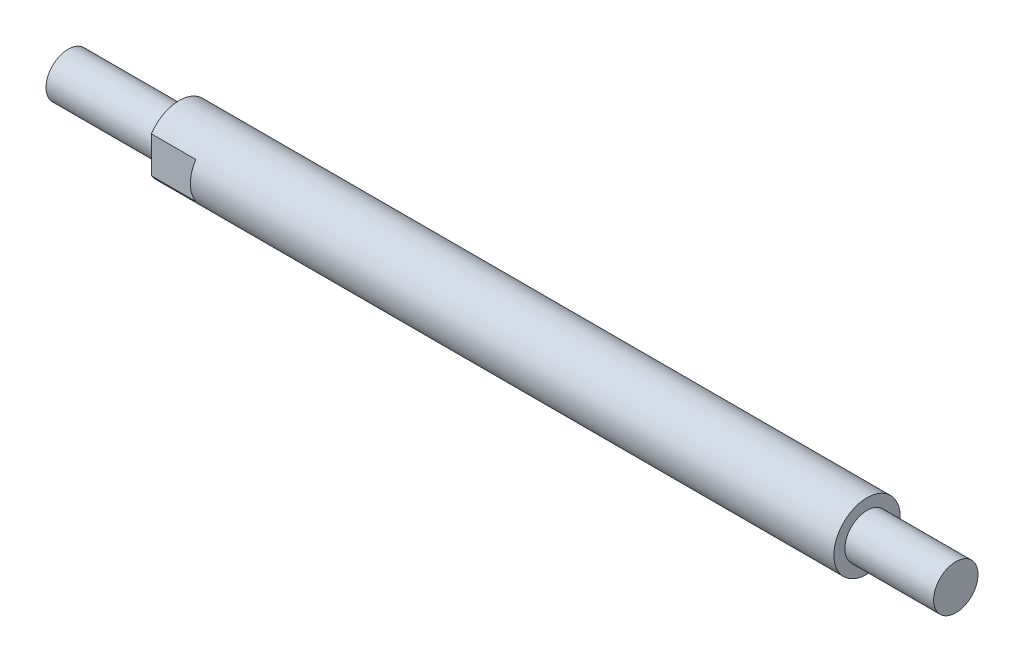
SolidWorks part; units mm, degrees
ref_plane "Front" through (0, 0, 0) normal (0, 0, 1) x (1, 0, 0)
ref_plane "Top" through (0, 0, 0) normal (0, 1, 0) x (1, 0, 0)
ref_plane "Right" through (0, 0, 0) normal (1, 0, 0) x (0, 0, -1)
sketch "Sketch1" plane through (0, 0, 0) normal (1, 0, 0) x (0, 0, -1)
  circle A0 centre (0, 0) radius 4.745
  dimension "D1" = 9.49
extrude "Base-Extrude" add sketch "Sketch1" along normal blind 114.3
sketch "Sketch2" plane through (114.3, 0, 0) normal (1, 0, 0) x (0, 0, -1)
  circle A0 centre (0, 0) radius 3.175
  dimension "D1" = 6.35
extrude "Boss-Extrude1" add sketch "Sketch2" along normal blind 12.7
cosmetic thread "Cosmetic Thread1" parameters "D2"=5.1054
sketch "Sketch3" plane through (0, 0, 0) normal (-1, 0, 0) x (0, 0, 1)
  circle A0 centre (0, 0) radius 3.175
  circle A2 centre (0, 0) radius 4.745
  circle A3 centre (0, 0) radius 4.745
  dimension "D1" = 6.35
  dimension "D2" = 0
extrude "Cut-Extrude1" cut sketch "Sketch3" against normal blind 15.875
sketch "Sketch4" plane through (15.875, 0, 0) normal (-1, 0, 0) x (0, 0, 1)
  line L1 (3.9688, 2.6008) -> (3.9688, -2.6008)
  line L3 (-3.9688, -2.6008) -> (-3.9688, 2.6008)
  line L4 (0, 4.7625) -> (0, 0) construction
  arc A1 (3.9688, -2.6008) -> (3.9688, 2.6008) centre (0, 0) ccw
  circle A2 centre (0, 0) radius 4.745
  arc A3 (-3.9688, 2.6008) -> (-3.9688, -2.6008) centre (0, 0) ccw
  dimension "D1" = 7.9375
  dimension "D2" = 0
extrude "Cut-Extrude2" cut sketch "Sketch4" against normal blind 6.35
